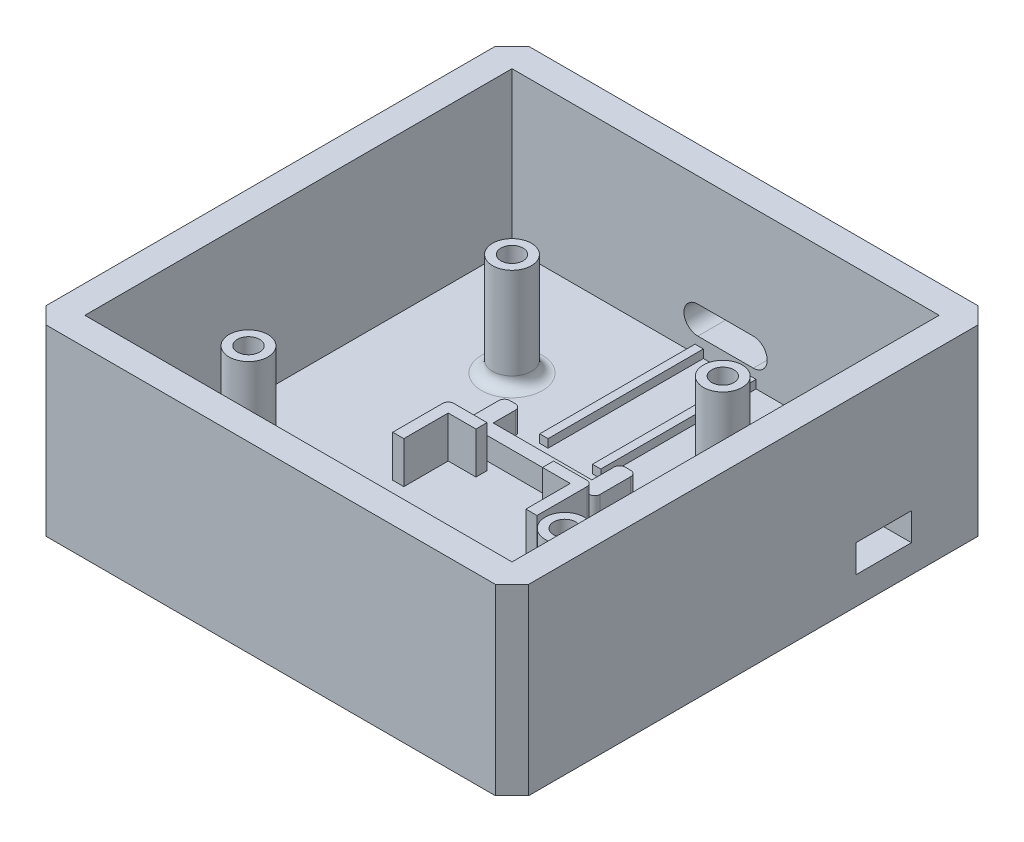
SolidWorks part; units mm, degrees
ref_plane "Front Plane" through (0, 0, 0) normal (0, 0, 1) x (1, 0, 0)
ref_plane "Top Plane" through (0, 0, 0) normal (0, 1, 0) x (1, 0, 0)
ref_plane "Right Plane" through (0, 0, 0) normal (1, 0, 0) x (0, 0, -1)
sketch "Sketch1" plane through (0, 0, 0) normal (0, 1, 0) x (1, 0, 0)
  line L1 (-38.5, -38.5) -> (38.5, -38.5)
  line L2 (-38.5, -38.5) -> (-38.5, 38.5)
  line L3 (-38.5, 38.5) -> (38.5, 38.5)
  line L4 (38.5, -38.5) -> (38.5, 38.5)
  line L5 (-38.5, -38.5) -> (38.5, 38.5) construction
  line L6 (-38.5, 38.5) -> (38.5, -38.5) construction
  point P0 (0, 0)
  dimension "D1" = 77
extrude "Boss-Extrude1" add sketch "Sketch1" along normal blind 5
sketch "Sketch2" plane through (0, 0, 0) normal (0, 1, 0) x (1, 0, 0)
  line L20 (38.5, -38.5) -> (38.5, 38.5) construction
  line L21 (38.5, 38.5) -> (-38.5, 38.5) construction
  line L22 (-38.5, 38.5) -> (-38.5, -38.5) construction
  line L23 (-38.5, -38.5) -> (38.5, -38.5) construction
  line L24 (43.5, -43.5) -> (43.5, 43.5)
  line L25 (43.5, 43.5) -> (-43.5, 43.5)
  line L26 (-43.5, 43.5) -> (-43.5, -43.5)
  line L27 (-43.5, -43.5) -> (43.5, -43.5)
  line L28 (43.5, -43.5) -> (43.5, 43.5)
  line L29 (43.5, 43.5) -> (-43.5, 43.5)
  line L30 (-43.5, 43.5) -> (-43.5, -43.5)
  line L31 (-43.5, -43.5) -> (43.5, -43.5)
  line L32 (38.5, -38.5) -> (38.5, 38.5)
  line L33 (38.5, 38.5) -> (-38.5, 38.5)
  line L34 (-38.5, 38.5) -> (-38.5, -38.5)
  line L35 (-38.5, -38.5) -> (38.5, -38.5)
  dimension "D1" = 5
extrude "Boss-Extrude2" add sketch "Sketch2" along normal blind 33
sketch "Sketch3" plane through (0, 5, 0) normal (0, 1, 0) x (1, 0, 0)
  line L0 (28.5, -19) -> (-28.5, -19) construction
  line L2 (19, 19) -> (-19, 19) construction
  circle A2 centre (-28.5, -19) radius 2
  circle A3 centre (28.5, -19) radius 2
  circle A4 centre (19, 19) radius 2
  circle A5 centre (-19, 19) radius 2
  circle A6 centre (-28.5, -19) radius 3.5
  circle A7 centre (-19, 19) radius 3.5
  circle A8 centre (28.5, -19) radius 3.5
  circle A9 centre (19, 19) radius 3.5
  point P0 (0, 0)
  point P1 (0, 0)
  point P2 (0, 19)
  point P17 (0, -19)
  dimension "D3" = 1.5
  dimension "D4" = 19
  dimension "D1" = 4
  dimension "D2" = 38
  dimension "D5" = 57
  dimension "D6" = 19
extrude "Boss-Extrude4" add sketch "Sketch3" along normal offset from surface (18.5 mm away) 9.5 up to face at (0, 33, 0)
sketch "Sketch11" plane through (0, 5, 0) normal (0, 1, 0) x (1, 0, 0)
  line L0 (-10, -31.5) -> (-10, -1.5)
  line L6 (-11, -32.5) -> (11, -32.5)
  line L7 (-11, -32.5) -> (-11, -0.5)
  line L8 (-11, -0.5) -> (11, -0.5)
  line L9 (11, -32.5) -> (11, -0.5)
  line L10 (-11, -32.5) -> (11, -0.5) construction
  line L11 (-11, -0.5) -> (11, -32.5) construction
  line L12 (38.5, 38.5) -> (-38.5, 38.5) construction
  line L13 (-8.89, 38.5) -> (8.89, 38.5) construction
  line L14 (-8.89, 38.5) -> (-8.89, 5.5) construction
  line L15 (-8.89, 5.5) -> (8.89, 5.5) construction
  line L16 (8.89, 38.5) -> (8.89, 5.5) construction
  line L17 (-8.89, 38.5) -> (8.89, 5.5) construction
  line L18 (-8.89, 5.5) -> (8.89, 38.5) construction
  line L27 (-10, -1.5) -> (10, -1.5)
  line L28 (10, -31.5) -> (10, -1.5)
  line L29 (-10, -31.5) -> (10, -31.5)
  line L30 (0, -18.15) -> (0, 18.15) construction
  line L31 (4, 38.5) -> (5.5, 38.5)
  line L32 (4, 38.5) -> (4, 10.5)
  line L33 (4, 10.5) -> (5.5, 10.5)
  line L34 (5.5, 38.5) -> (5.5, 10.5)
  line L35 (-4, 10.5) -> (-5.5, 10.5)
  line L36 (-5.5, 38.5) -> (-5.5, 10.5)
  line L37 (-4, 38.5) -> (-5.5, 38.5)
  line L38 (-4, 38.5) -> (-4, 10.5)
  line L39 (-38.5, -38.5) -> (38.5, -38.5) construction
  point P1 (0, 22)
  point P6 (0, -16.5)
  dimension "D1" = 33
  dimension "D2" = 17.78
  dimension "D3" = 1
  dimension "D4" = 20
  dimension "D5" = 6
  dimension "D6" = 30
  dimension "D7" = 4
  dimension "D8" = 1.5
  dimension "D9" = 5
extrude "Boss-Extrude7" add sketch "Sketch11" along normal blind 1.5 contours L35 L36 L37 L38 | L32 L31 L34 L33
sketch "Sketch17" plane through (0, 5, 0) normal (0, 1, 0) x (1, 0, 0)
  line L0 (-8.89, 10.5) -> (-8.89, 5.5)
  line L1 (-8.89, 38.5) -> (-8.89, 5.5) construction
  line L2 (-8.89, 5.5) -> (8.89, 5.5)
  line L3 (8.89, 5.5) -> (8.89, 10.5)
  line L4 (8.89, 38.5) -> (8.89, 5.5) construction
  line L5 (8.89, 10.5) -> (11.89, 10.5)
  line L6 (11.89, 10.5) -> (11.89, 3)
  line L7 (11.89, 3) -> (-11.89, 3)
  line L8 (-11.89, 3) -> (-11.89, 10.5)
  line L9 (-11.89, 10.5) -> (-8.89, 10.5)
  dimension "D1" = 3
  dimension "D2" = 2.5
  dimension "D3" = 5
extrude "Boss-Extrude8" add sketch "Sketch17" along normal blind 4
sketch "Sketch4" plane through (0, 0, 0) normal (1, 0, 0) x (0, 0, -1)
  line L0 (0, 0) -> (0, 33) construction
  line L1 (-43.5, 33) -> (43.5, 33) construction
sketch "Sketch7" plane through (0, 0, 0) normal (0, -1, 0) x (1, 0, 0)
  line L0 (43.5, -43.5) -> (-43.5, -43.5) construction
  line L1 (-43.5, -43.5) -> (-43.5, 43.5) construction
  line L2 (0, 0) -> (-23.5, -23.5) construction
  circle A0 centre (-23.5, -23.5) radius 4
  circle A1 centre (-23.5, 23.5) radius 4
  circle A2 centre (23.5, 23.5) radius 4
  circle A3 centre (23.5, -23.5) radius 4
  point P6 (0, 0)
  dimension "D1" = 8
  dimension "D2" = 20
  dimension "D3" = 20
  dimension "D4" = 4
extrude "Cut-Extrude1" cut sketch "Sketch7" against normal blind 2
sketch "Sketch10" plane through (0, 0, -38.5) normal (0, 0, -1) x (-1, 0, 0)
  line L0 (-5, 10.5) -> (5, 10.5) construction
  line L1 (-5, 13) -> (5, 13)
  line L2 (-5, 8) -> (5, 8)
  line L3 (-38.5, 5) -> (-5.5, 5) construction
  line L4 (-38.5, 5) -> (-5.5, 5) construction
  line L5 (4, 6.5) -> (5.5, 6.5) construction
  arc A1 (-5, 13) -> (-5, 8) centre (-5, 10.5) ccw
  arc A2 (5, 8) -> (5, 13) centre (5, 10.5) ccw
  point P2 (0, 10.5)
  dimension "D1" = 10
  dimension "D2" = 5
  dimension "D3" = 4
extrude "Cut-Extrude2" cut sketch "Sketch10" along normal up to surface (5 mm away) up to face at (0, 16.5, -43.5)
sketch "Sketch16" plane through (38.5, 0, 0) normal (-1, 0, 0) x (0, 0, 1)
  line L0 (38.5, 5) -> (-38.5, 5) construction
  line L1 (-28.5, 5) -> (-18.5, 5)
  line L2 (-28.5, 5) -> (-28.5, 10)
  line L3 (-28.5, 10) -> (-18.5, 10)
  line L4 (-18.5, 5) -> (-18.5, 10)
  dimension "D1" = 10
  dimension "D2" = 5
  dimension "D3" = 10
extrude "Cut-Extrude3" cut sketch "Sketch16" against normal up to surface (5 mm away) up to face at (43.5, 16.5, 0)
sketch "Sketch15" plane through (0, 5, 0) normal (0, 1, 0) x (1, 0, 0)
  line L0 (-11, -0.5) -> (-11, -8.5)
  line L1 (-11, -32.5) -> (-11, -0.5) construction
  line L2 (-11, -8.5) -> (-13, -8.5)
  line L3 (-13, -8.5) -> (-13, 1.5)
  line L4 (-13, 1.5) -> (-6, 1.5)
  line L5 (-6, 1.5) -> (-6, -0.5)
  line L6 (-11, -0.5) -> (11, -0.5) construction
  line L7 (-6, -0.5) -> (-11, -0.5)
  line L8 (-13, -24.5) -> (-11, -24.5)
  line L9 (-11, -24.5) -> (-11, -32.5)
  line L10 (-11, -32.5) -> (-6, -32.5)
  line L11 (-11, -32.5) -> (11, -32.5) construction
  line L12 (-6, -32.5) -> (-6, -34.5)
  line L13 (-6, -34.5) -> (-13, -34.5)
  line L14 (-13, -24.5) -> (-13, -34.5)
  line L15 (0, -18.15) -> (0, 18.15) construction
  line L16 (13, -24.5) -> (11, -24.5)
  line L17 (11, -24.5) -> (11, -32.5)
  line L18 (11, -32.5) -> (6, -32.5)
  line L19 (6, -32.5) -> (6, -34.5)
  line L20 (6, -34.5) -> (13, -34.5)
  line L21 (13, -24.5) -> (13, -34.5)
  line L22 (6, 1.5) -> (6, -0.5)
  line L23 (13, 1.5) -> (6, 1.5)
  line L24 (13, -8.5) -> (13, 1.5)
  line L25 (11, -8.5) -> (13, -8.5)
  line L26 (11, -0.5) -> (11, -8.5)
  line L27 (6, -0.5) -> (11, -0.5)
  point P13 (-15, -34.0838)
  point P21 (-7.8073, -33.9227)
  point P22 (0, 0)
  point P23 (0, 0)
  point P24 (-15, -25.5691)
  point P25 (-15, -26.7886)
  dimension "D1" = 7
  dimension "D2" = 10
  dimension "D4" = 2
extrude "Boss-Extrude6" add sketch "Sketch15" along normal blind 7.5 contours L7 L0 L2 L3 L4 L5 | L22 L27 L26 L25 L24 L23 | L14 L13 L12 L10 L9 L8 | L16 L17 L18 L19 L20 L21
fillet "Fillet1" radius 2 4 edges at (28.5, 5, 15.5) (19, 5, -22.5) (-28.5, 5, 15.5) (-19, 5, -22.5)
fillet "Fillet2" radius 1 10 edges at (-13, 8.75, 34.5) (13, 8.75, 34.5) (13, 8.75, -1.5) (-13, 8.75, -1.5) (-11.89, 7, -10.5) (11.89, 7, -10.5) (11.89, 7, -3) (-11.89, 7, -3) (8.89, 7, -10.5) (-8.89, 7, -10.5)
chamfer "Chamfer1" distance 3 angle 45 4 edges at (43.5, 16.5, -43.5) (-43.5, 16.5, 43.5) (43.5, 16.5, 43.5) (-43.5, 16.5, -43.5)
